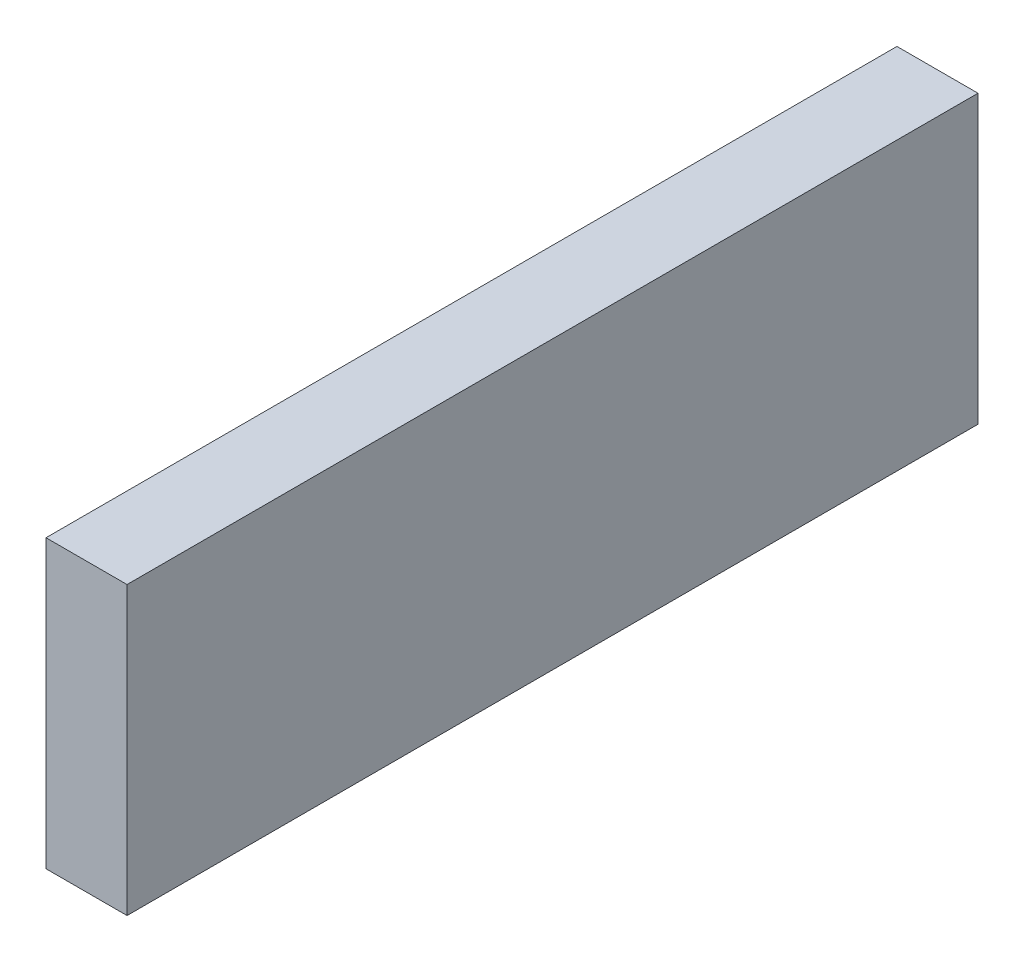
SolidWorks part; units mm, degrees
ref_plane "Спереди" through (0, 0, 0) normal (0, 0, 1) x (1, 0, 0)
ref_plane "Сверху" through (0, 0, 0) normal (0, 1, 0) x (1, 0, 0)
ref_plane "Справа" through (0, 0, 0) normal (1, 0, 0) x (0, 0, -1)
sketch "Эскиз1" plane through (0, 0, 0) normal (1, 0, 0) x (0, 0, -1)
  line L1 (0, 0) -> (42, 0)
  line L2 (0, 0) -> (0, 14.15)
  line L3 (0, 14.15) -> (42, 14.15)
  line L4 (42, 0) -> (42, 14.15)
  dimension "D1" = 42
  dimension "D2" = 14.15
extrude "Бобышка-Вытянуть1" add sketch "Эскиз1" along normal blind 4
